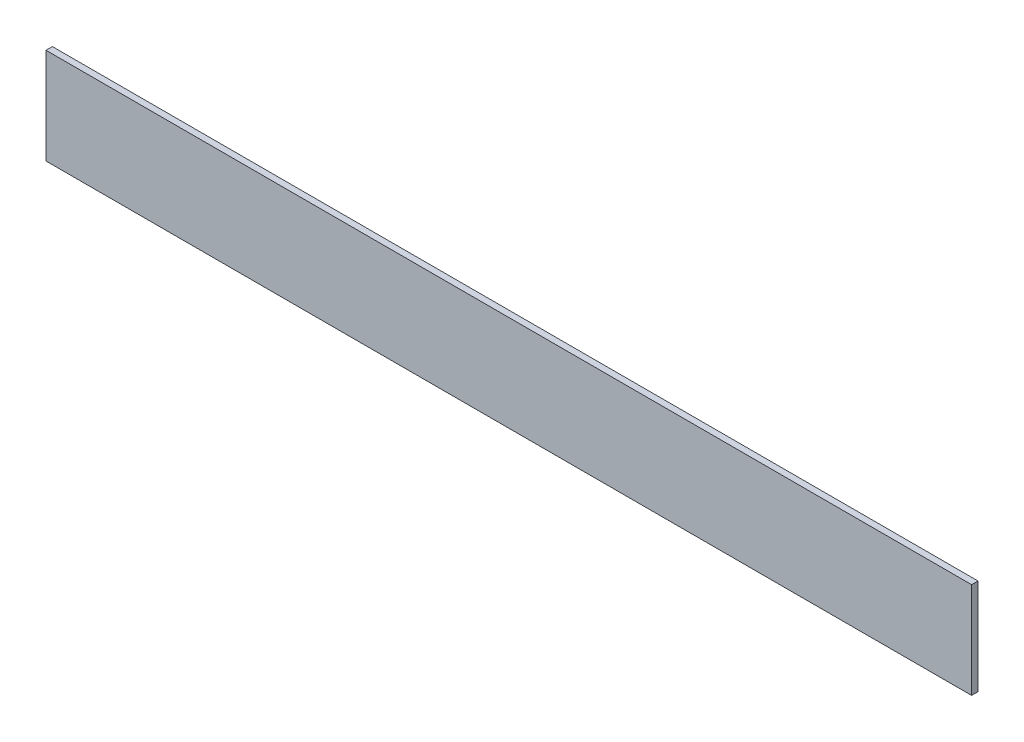
SolidWorks part; units mm, degrees
material "Custom Plastic"
ref_plane "X-Y Datum" through (0, 0, 0) normal (0, 0, 1) x (1, 0, 0)
ref_plane "X-Z Datum" through (0, 0, 0) normal (0, 1, 0) x (1, 0, 0)
ref_plane "Y-Z Datum" through (0, 0, 0) normal (1, 0, 0) x (0, 0, -1)
sketch "Sketch1" plane through (0, 0, 0) normal (0, 0, 1) x (1, 0, 0)
  line L1 (-229.745, 23.8125) -> (229.745, 23.8125)
  line L2 (-229.745, 23.8125) -> (-229.745, -23.8125)
  line L3 (-229.745, -23.8125) -> (229.745, -23.8125)
  line L4 (229.745, 23.8125) -> (229.745, -23.8125)
  line L5 (-229.745, 23.8125) -> (229.745, -23.8125) construction
  line L6 (-229.745, -23.8125) -> (229.745, 23.8125) construction
  point P0 (0, 0)
  dimension "D1" = 459.49
  dimension "D2" = 47.625
extrude "Boss-Extrude1" add sketch "Sketch1" along normal blind 3.175
